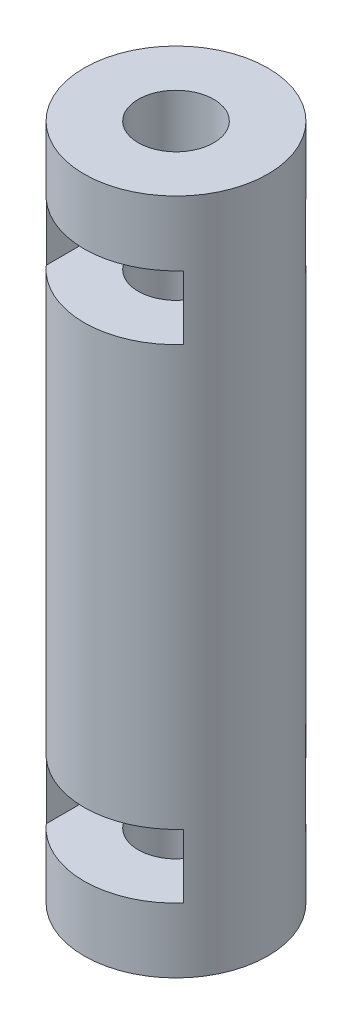
SolidWorks part; units mm, degrees
material "ABS"
ref_plane "Front Plane" through (0, 0, 0) normal (0, 0, 1) x (1, 0, 0)
ref_plane "Top Plane" through (0, 0, 0) normal (0, 1, 0) x (1, 0, 0)
ref_plane "Right Plane" through (0, 0, 0) normal (1, 0, 0) x (0, 0, -1)
sketch "Sketch1" plane through (0, 0, 0) normal (0, 1, 0) x (1, 0, 0)
  circle A0 centre (0, 0) radius 4.75
  circle A1 centre (0, 0) radius 1.95
  dimension "D1" = 9.5
  dimension "D2" = 3.9
extrude "Boss-Extrude1" add sketch "Sketch1" along normal blind 35
sketch "Sketch2" plane through (0, 0, 0) normal (0, 0, 1) x (1, 0, 0)
  line L0 (0, 35) -> (0, 0) construction
  line L1 (4.75, 35) -> (-4.75, 35) construction
  line L2 (-4.75, 17.5) -> (9.2464, 17.5) construction
  line L3 (-3.55, 28.35) -> (3.55, 28.35)
  line L4 (-3.55, 28.35) -> (-3.55, 31.65)
  line L5 (-3.55, 31.65) -> (3.55, 31.65)
  line L6 (3.55, 28.35) -> (3.55, 31.65)
  line L7 (-3.55, 28.35) -> (3.55, 31.65) construction
  line L8 (-3.55, 31.65) -> (3.55, 28.35) construction
  line L9 (-4.75, 35) -> (-4.75, 0) construction
  line L10 (3.55, 6.65) -> (3.55, 3.35)
  line L11 (-3.55, 3.35) -> (3.55, 3.35)
  line L12 (-3.55, 6.65) -> (-3.55, 3.35)
  line L13 (-3.55, 6.65) -> (3.55, 6.65)
  point P5 (0, 30)
  dimension "D1" = 3.3
  dimension "D2" = 7.1
  dimension "D3" = 5
extrude "Cut-Extrude1" cut sketch "Sketch2" against normal through all both and the other way through all
